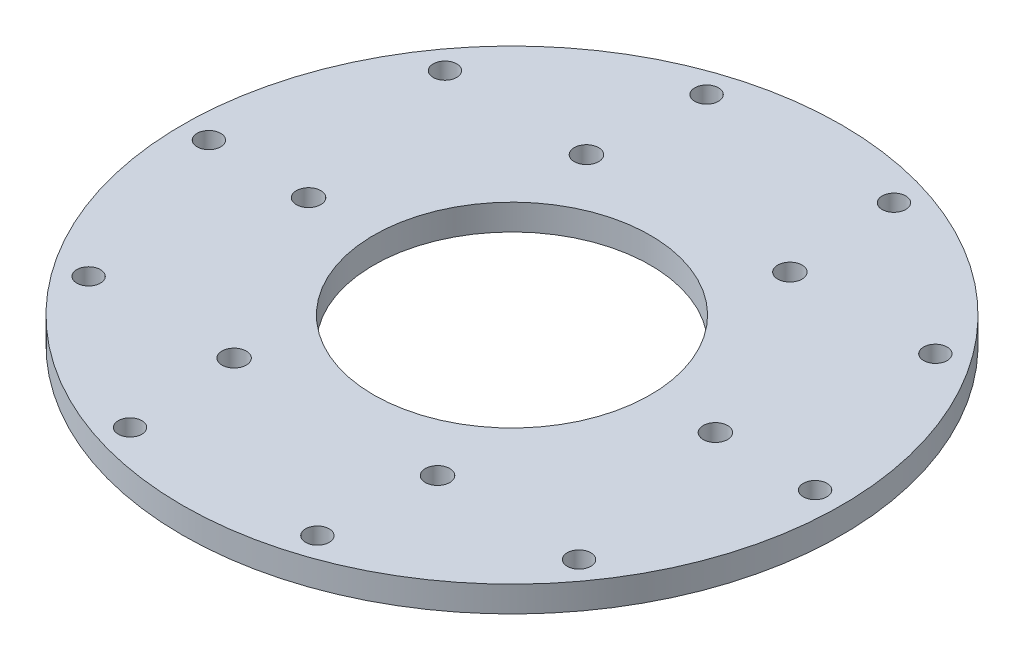
SolidWorks part; units mm, degrees
material "1060 Alloy"
ref_plane "Front Plane" through (0, 0, 0) normal (0, 0, 1) x (1, 0, 0)
ref_plane "Top Plane" through (0, 0, 0) normal (0, 1, 0) x (1, 0, 0)
ref_plane "Right Plane" through (0, 0, 0) normal (1, 0, 0) x (0, 0, -1)
sketch "Sketch2" plane through (0, 0, 0) normal (0, 1, 0) x (1, 0, 0)
  circle A0 centre (0, 0) radius 17
  circle A1 centre (0, 0) radius 40.5
  circle A2 centre (0, 0) radius 37.25 construction
  circle A3 centre (-37.25, 0) radius 1.45
  circle A4 centre (0, 0) radius 25 construction
  circle A5 centre (-25, 0) radius 1.5
  circle A6 centre (-12.5, 21.6506) radius 1.5
  circle A7 centre (12.5, 21.6506) radius 1.5
  circle A8 centre (25, 0) radius 1.5
  circle A9 centre (12.5, -21.6506) radius 1.5
  circle A10 centre (-12.5, -21.6506) radius 1.5
  circle A11 centre (-30.1359, 21.895) radius 1.45
  circle A12 centre (-11.5109, 35.4269) radius 1.45
  circle A13 centre (11.5109, 35.4269) radius 1.45
  circle A14 centre (30.1359, 21.895) radius 1.45
  circle A15 centre (37.25, 0) radius 1.45
  circle A16 centre (30.1359, -21.895) radius 1.45
  circle A17 centre (11.5109, -35.4269) radius 1.45
  circle A18 centre (-11.5109, -35.4269) radius 1.45
  circle A19 centre (-30.1359, -21.895) radius 1.45
  point P22 (0, 0)
  point P33 (0, 0)
  dimension "D1" = 3
  dimension "D2" = 50
  dimension "D4" = 34
  dimension "D5" = 81
  dimension "D6" = 74.5
  dimension "D7" = 2.9
  dimension "D3" = 6
  dimension "D8" = 10
extrude "Boss-Extrude1" add sketch "Sketch2" along normal blind 3.175
equation "\"Stator_OD\"= 60'No Tolerance given"
equation "\"A\"=35.81 'taken off spec sheet for 06808 (A)"
equation "\"Rotor_ID\"= 30'No Tolerance Given"
equation "\"back_bearing_Thickness\"= 5'-0.12"
equation "\"back_bearing_OD\"= 24'-0.009 https://www.mcmaster.com/5972K155/"
equation "\"Stator_Gap\"= 0.0375'+- 0.0125 (From 1.3.3.1 Kollmorgen manual)"
equation "\"Back_mount_hole\"= 1.75'To be tapped to M2 (USE LOCKTITE)"
equation "\"facePlate_Mount_Hole\"= 2.75'To be tapped to M3"
equation "\"final_shaftD\"= 12'To fit in harmonic"
equation "\"final_shaftL\"= 5.25+3+\"sheet_thick\"+\"connector_thick\"-3+\"harmon_coupleL\"+0.5-\"shaft_Ladjust\"'length to make everything nice and aligned"
equation "\"back_bearing_ID\"= 15'"
equation "\"back_bearing_IDOD\"= 16.5'measured off CAD, actually 16.75, but rounded down to nicer number"
equation "\"rotor_shaftD\"= \"Rotor_ID\" - (\"rotor-shaft_gap\")*2'"
equation "\"front_bearing_ID\"= 12'https://www.mcmaster.com/5972K154/"
equation "\"front_bearing_OD\"= 21'-0.009"
equation "\"front_bearing_IDOD\"= 13.5'Measured off CAD. Actually 13.75, but rounded down"
equation "\"rotor-shaft_gap\" = 0.0185 '+-0.0065 (from manual)"
equation "\"front_bearing_Thickness\"= 5'-0.12"
equation "\"rotor_thickness\"= 2.4'measured off CAD"
equation "\"rotor_height\"= 32.86'+-0.075 taken off spec sheet for 06826 (C)"
equation "\"B\"= 26.3'+-0.35 taken off spec sheet for 06826"
equation "\"key_L\"= 20'-0.2 https://www.mcmaster.com/2977N19/"
equation "\"key_H\"= 4'-0.03"
equation "\"key_W\"= 4'-0.03"
equation "\"harmon_keyH\"= 13.8'+0.1 from drawing"
equation "\"harmon_coupleL\"= 21.5' taken from drawing https://www.harmonicdrive.net/_hd/content/caddownloads/dxf/csf-2uh-ulw_gearheads/CSF-17-xxx-2UH-ULW.pdf"
equation "\"harmon_diam\"= 81' from drawing"
equation "\"harmon_BCD\"= 74.5' from drawing"
equation "\"harmon_holeD1\"= 3.4' from drawing"
equation "\"harmon_holeD2\"= 3' from drawing"
equation "\"harmon_holeAng\"= 18' from drawing"
equation "\"sheet_thick\"= 1/8*25.4 'random, replace w actual sheet thickness when u feel like :)"
equation "\"D1@Sketch2\"=\"facePlate_Mount_Hole\"+0.25"
equation "\"D4@Sketch2\"=\"back_bearing_OD\"+10"
equation "\"D5@Sketch2\"=\"harmon_diam\""
equation "\"D6@Sketch2\"=\"harmon_BCD\""
equation "\"D7@Sketch2\"=\"harmon_holeD2\"-0.1"
equation "\"D1@Boss-Extrude1\"=\"sheet_thick\""
equation "\"nut-thickness\"= 5 'idk measure the ones in the shop and adjust"
equation "\"connector_thick\"= 10' random for now"
equation "\"shaft_Ladjust\"= 6.75' sorry. It's silly, but it works."
